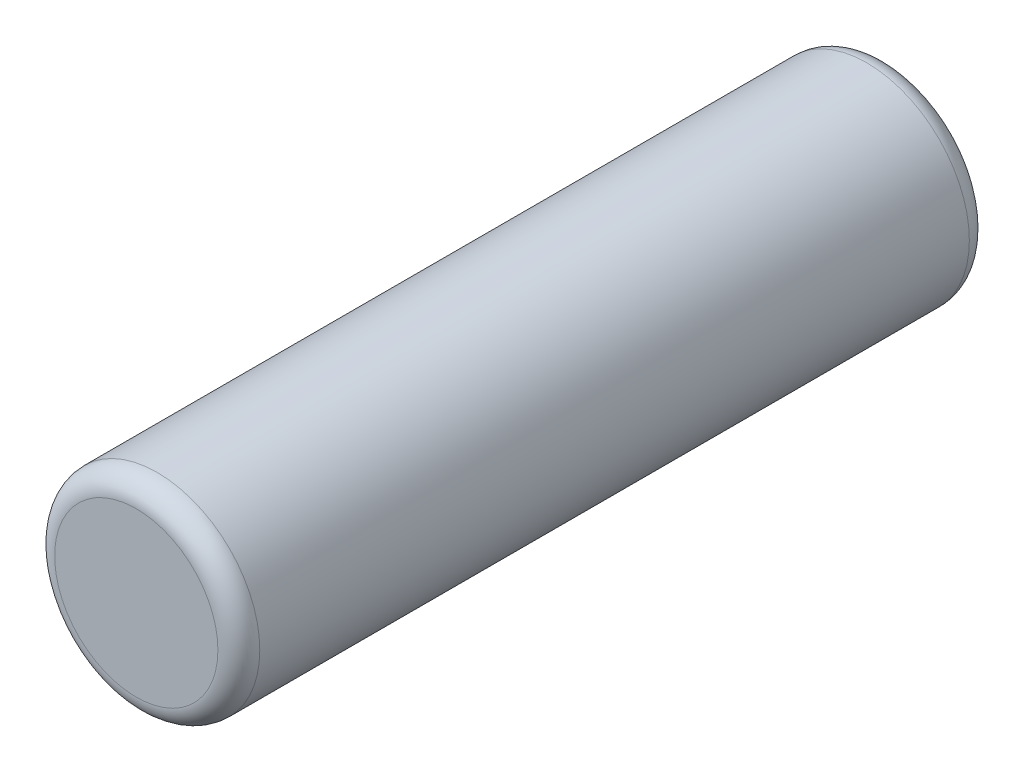
SolidWorks part; units mm, degrees
ref_plane "정면" through (0, 0, 0) normal (0, 0, 1) x (1, 0, 0)
ref_plane "윗면" through (0, 0, 0) normal (0, 1, 0) x (1, 0, 0)
ref_plane "우측면" through (0, 0, 0) normal (1, 0, 0) x (0, 0, -1)
sketch "스케치1" plane through (0, 0, 0) normal (0, 0, 1) x (1, 0, 0)
  circle A0 centre (0, 0) radius 2.45
  dimension "D1" = 4.9
extrude "보스-돌출1" add sketch "스케치1" along normal blind 17.95
fillet "필렛1" radius 0.5 2 edges at (2.45, 0, 0) (2.45, 0, 17.95)
